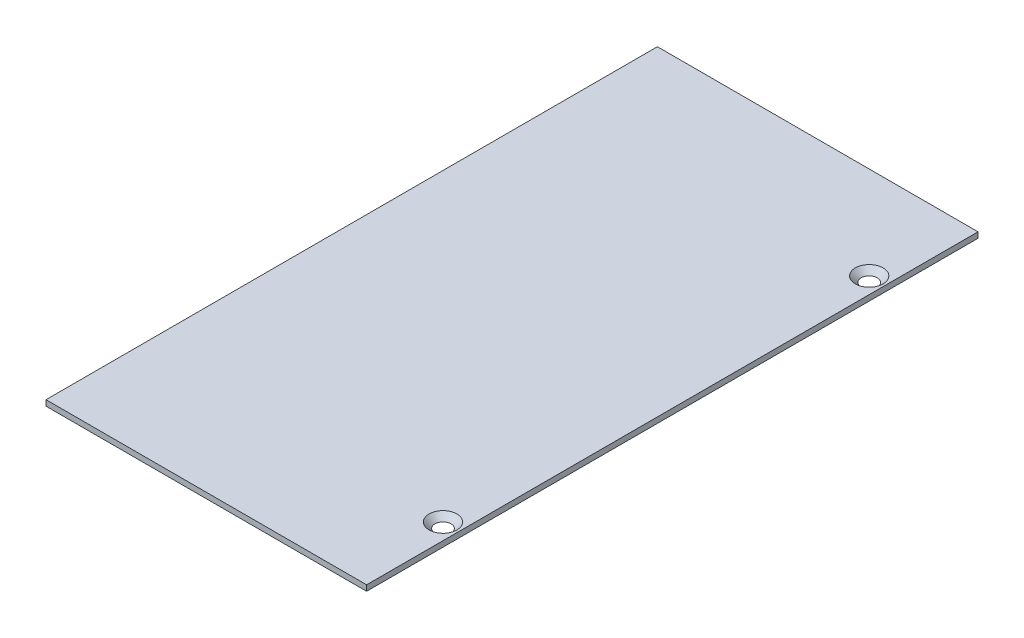
SolidWorks part; units mm, degrees
material "Plain Carbon Steel"
ref_plane "Front Plane" through (0, 0, 0) normal (0, 0, 1) x (1, 0, 0)
ref_plane "Top Plane" through (0, 0, 0) normal (0, 1, 0) x (1, 0, 0)
ref_plane "Right Plane" through (0, 0, 0) normal (1, 0, 0) x (0, 0, -1)
sketch "Sketch1" plane through (0, 0, 0) normal (0, 1, 0) x (1, 0, 0)
  line L1 (0, 0) -> (69.24, 0)
  line L2 (0, 0) -> (0, 132.04)
  line L3 (0, 132.04) -> (69.24, 132.04)
  line L4 (69.24, 0) -> (69.24, 132.04)
  dimension "D1" = 69.24
  dimension "D2" = 132.04
extrude "Boss-Extrude1" add sketch "Sketch1" along normal blind 1.2192
sketch "Sketch2" plane through (0, 1.2192, 0) normal (0, 1, 0) x (1, 0, 0)
  line L0 (69.24, 0) -> (69.24, 132.04) construction
  line L1 (69.24, 132.04) -> (0, 132.04) construction
  line L2 (0, 0) -> (69.24, 0) construction
  point P0 (65.74, 112.04)
  point P1 (65.74, 20)
  dimension "D1" = 3.5
  dimension "D2" = 3.5
  dimension "D3" = 20
  dimension "D4" = 20
hole_wizard "CSK for M3 Cross Countersunk Head Screw1" positions "Sketch3" profile "Sketch4" countersink size "M3" standard "AS"
sketch "Sketch3" plane through (0, 1.2192, 0) normal (0, 1, 0) x (1, 0, 0)
  point P0 (65.74, 112.04)
  point P3 (65.74, 20)
sketch "Sketch4" plane through (65.74, 1.2192, -112.04) normal (1, 0, 0) x (0, 0, 1)
  line L0 (0, 0) -> (0, 71.7815)
  line L1 (0, 71.7815) -> (1.7, 70.76)
  line L2 (1.7, 70.76) -> (1.7, 1.2554)
  line L3 (1.7, 1.2554) -> (3, 0)
  line L5 (3, 0) -> (0, 0)
  line L6 (-1.7, 1.2554) -> (-3, 0) construction
  line L10 (0, 71.7815) -> (-1.7, 70.76) construction
  line L11 (0, -6.35) -> (0, 107.95) construction
  dimension "Hole Dia." = 3.4
  dimension "Hole Depth" = 70.76
  dimension "Near C'Sink Dia." = 6
  dimension "Near C'Sink Angle" = 92
  dimension "Drill Angle" = 118
